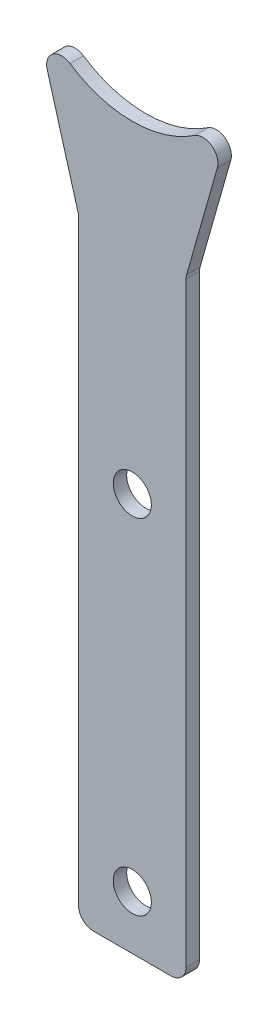
SolidWorks part; units mm, degrees
material "ASTM A36 Steel"
ref_plane "X-Y Datum" through (0, 0, 0) normal (0, 0, 1) x (1, 0, 0)
ref_plane "X-Z Datum" through (0, 0, 0) normal (0, 1, 0) x (1, 0, 0)
ref_plane "Y-Z Datum" through (0, 0, 0) normal (1, 0, 0) x (0, 0, -1)
sketch "Sketch1" plane through (0, 0, 0) normal (0, 0, 1) x (1, 0, 0)
  line L0 (-4.0676, 19.9987) -> (-4.0676, 21.2687) construction
  line L1 (1.1824, 19.9987) -> (1.1824, 19.9921) construction
  line L2 (-4.0676, 19.9987) -> (-4.0676, 18.7287) construction
  line L3 (1.1824, 19.9987) -> (1.1824, 17.4521) construction
  line L4 (-4.0676, -20.6413) -> (-4.0676, -19.2443) construction
  line L5 (1.1824, -20.6413) -> (1.1824, -20.5208) construction
  line L6 (-4.0676, -20.6413) -> (-4.0676, -21.7843) construction
  line L7 (1.1824, -20.6413) -> (1.1824, -23.0608) construction
  line L8 (-4.0676, -20.6413) -> (-6.0996, -20.6413) construction
  line L10 (1.1824, -20.6413) -> (3.2144, -20.6413) construction
  line L11 (-14.1448, 67.6864) -> (-7.7926, 45.3987)
  line L12 (4.9074, -26.9913) -> (-7.7926, -26.9913)
  line L13 (4.9074, -26.9913) -> (4.9074, 45.3987)
  line L15 (-7.7926, -26.9913) -> (-7.7926, 45.3987)
  line L16 (4.9074, 45.3987) -> (11.2595, 67.6864)
  circle A0 centre (-1.4426, 19.9987) radius 2.625
  circle A1 centre (-1.4426, -20.6413) radius 2.625
  arc A3 (-14.1448, 67.6864) -> (11.2595, 67.6864) centre (-1.4426, 71.3067) ccw
  circle A4 centre (-1.4426, 71.3067) radius 13.208
  point P2 (-1.4426, 58.0987)
  dimension "D1" = 12.7
  dimension "D5" = 26.416
  dimension "D2" = 6.35
  dimension "D3" = 40.64
  dimension "D4" = 12.7
  dimension "D6" = 72.39
extrude "Boss-Extrude1" add sketch "Sketch1" along normal blind 1.5875 contours A3 L11 L15 L12 L13 L16 A1 A0 | A0 | A1
fillet "Fillet1" radius 1.778 6 edges at (-7.7926, -26.9913, 0.7937) (4.9074, -26.9913, 0.7937) (-7.7926, 45.3987, 0.7937) (4.9074, 45.3987, 0.7937) (-14.1448, 67.6864, 0.7937) (11.2595, 67.6864, 0.7937)
hole_wizard "M4 Clearance Hole1" positions "Sketch2" profile "Sketch3" hole size "M4" standard "ANSI Metric" end condition through all
sketch "Sketch2" plane through (0, 0, 1.5875) normal (0, 0, 1) x (1, 0, 0)
  point P0 (-1.4426, -20.6413)
  point P3 (-1.4426, 19.9987)
sketch "Sketch3" plane through (-1.4426, -20.6413, 1.5875) normal (1, 0, 0) x (0, -1, 0)
  line L0 (0, 0) -> (0, 1.5875)
  line L1 (0, 1.5875) -> (2.25, 1.5875)
  line L2 (2.25, 1.5875) -> (2.25, 0)
  line L5 (2.25, 0) -> (0, 0)
  line L11 (0, -6.35) -> (0, 107.95) construction
  dimension "Thru Hole Dia." = 4.5
  dimension "Thru Hole Depth" = 1.5875
